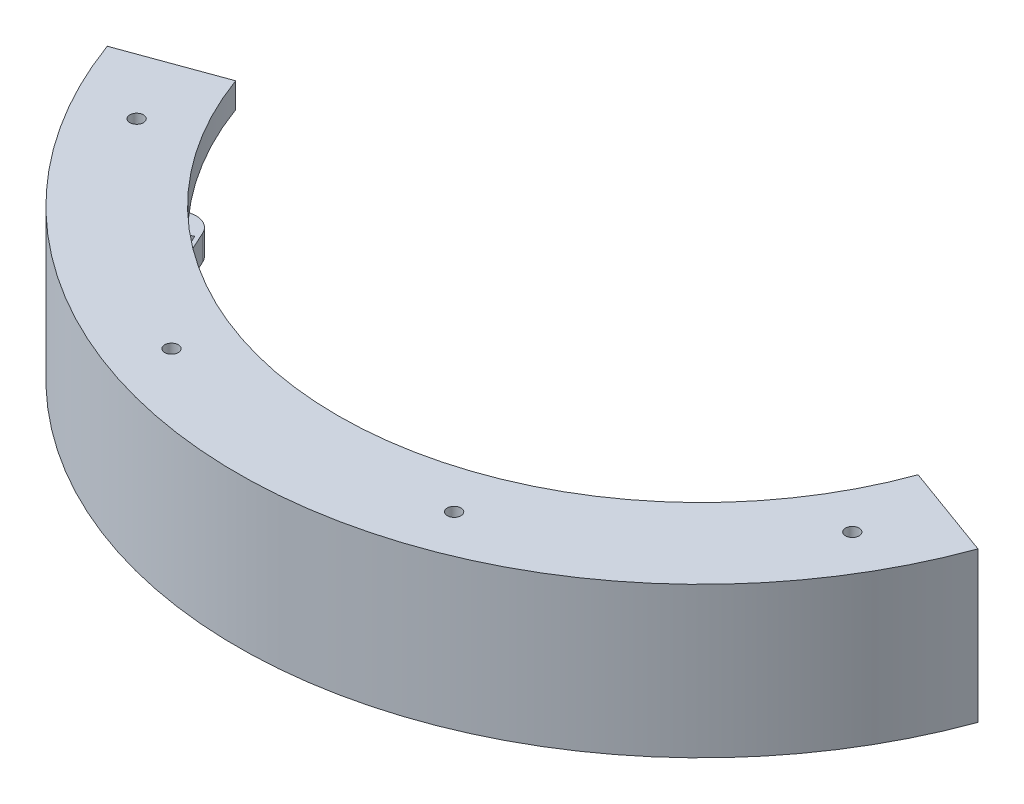
SolidWorks part; units mm, degrees
ref_plane "Front" through (0, 0, 0) normal (0, 0, 1) x (1, 0, 0)
ref_plane "Top" through (0, 0, 0) normal (0, 1, 0) x (1, 0, 0)
ref_plane "Right" through (0, 0, 0) normal (1, 0, 0) x (0, 0, -1)
sketch "Sketch1" plane through (0, 0, 0) normal (0, 1, 0) x (1, 0, 0)
  line L0 (-110.3904, -40.1788) -> (-86.5222, -31.4915)
  line L1 (86.5222, -31.4915) -> (110.3904, -40.1788)
  line L2 (-86.5222, -31.4915) -> (0, 0) construction
  line L3 (0, 0) -> (86.5222, -31.4915) construction
  line L4 (0, 0) -> (0, -117.475) construction
  line L5 (-86.5222, -31.4915) -> (0, -117.475) construction
  line L6 (0, -117.475) -> (86.5222, -31.4915) construction
  arc A0 (-110.3904, -40.1788) -> (110.3904, -40.1788) centre (0, 0) ccw
  arc A1 (-86.5222, -31.4915) -> (86.5222, -31.4915) centre (0, 0) ccw
  dimension "D1" = 25.4
  dimension "D2" = 117.475
  dimension "D3" = 140
extrude "Boss-Extrude1" add sketch "Sketch1" against normal blind 38.1
ref_plane "Plane1" through (86.5222, 0, 31.4915) normal (-0.342, 0, 0.9397) x (0.9397, 0, 0.342)
sketch "Sketch4" plane through (86.5222, 0, 31.4915) normal (-0.342, 0, 0.9397) x (0.9397, 0, 0.342)
  line L0 (0, -6.35) -> (19.05, -6.35)
  line L1 (0, -38.1) -> (0, 0) construction
  line L2 (19.05, -6.35) -> (19.05, -31.75)
  line L3 (19.05, -31.75) -> (0, -31.75)
  line L4 (0, -31.75) -> (0, -6.35)
  line L5 (25.4, -38.1) -> (25.4, 0) construction
  line L6 (25.4, -38.1) -> (0, -38.1) construction
  line L7 (25.4, 0) -> (0, 0) construction
  point P8 (12.7, -38.1)
  dimension "D1" = 6.35
  dimension "D2" = 6.35
  dimension "D3" = 6.35
ref_axis "Axis1" through (0, -38.1, 0) along (0, 1, 0)
revolve "Cut-Revolve1" cut sketch "Sketch4" about axis through (0, -38.1, 0) along (0, 1, 0)
sketch "Sketch5" plane through (0, -31.75, 0) normal (0, 1, 0) x (1, 0, 0)
  line L0 (98.3014, -45.3981) -> (88.6213, -40.6089)
  line L1 (98.3014, -45.3981) -> (95.7295, -50.5966)
  line L2 (95.7295, -50.5966) -> (86.0494, -45.8075)
  line L3 (86.0494, -45.8075) -> (88.6213, -40.6089)
  line L6 (0, 0) -> (105.2935, -52.0928) construction
  arc A0 (-110.3904, -40.1788) -> (110.3904, -40.1788) centre (0, 0) ccw construction
  arc A2 (-86.5222, -31.4915) -> (86.5222, -31.4915) centre (0, 0) ccw construction
  dimension "D1" = 5.8
  dimension "D2" = 10.8
  dimension "D3" = 2.9
  dimension "D4" = 97.4393
extrude "Cut-Extrude1" cut sketch "Sketch5" along normal up to surface (6.35 mm away)
pattern_circular "CirPattern1" count 13 every 11.667 about axis through (0, 0, 0) along (0, 1, 0) of "Cut-Extrude1"
sketch "Sketch10" plane through (0, 0, 0) normal (0, 1, 0) x (1, 0, 0)
  line L0 (0, 0) -> (101.7363, -58.7375) construction
  line L1 (39.1435, -14.2471) -> (133.9009, -48.7359) construction
  arc A0 (-110.3904, -40.1788) -> (110.3904, -40.1788) centre (0, 0) ccw construction
  circle A1 centre (0, 0) radius 104.775
  arc A2 (-86.5222, -31.4915) -> (86.5222, -31.4915) centre (0, 0) ccw construction
  dimension "D2" = 12.7
  dimension "D1" = 10
hole_wizard "#8-32 Tapped Hole1" positions "Sketch12" profile "Sketch11" tap size "#8-32" standard "ANSI Inch"
sketch "Sketch12" plane through (0, 0, 0) normal (0, 1, 0) x (1, 0, 0)
  line L0 (0, 0) -> (101.7363, -58.7375) construction
  circle A0 centre (0, 0) radius 104.775 construction
  point P0 (90.7378, -52.3875)
sketch "Sketch11" plane through (90.7378, 0, 52.3875) normal (1, 0, 0) x (0, 0, 1)
  line L0 (0, 0) -> (0, 11.7058)
  line L1 (0, 11.7058) -> (1.7272, 10.668)
  line L2 (1.7272, 10.668) -> (1.7272, 0)
  line L5 (1.7272, 0) -> (0, 0)
  line L10 (0, 11.7058) -> (-1.7272, 10.668) construction
  line L11 (0, -6.35) -> (0, 107.95) construction
  dimension "Tap Drill Dia." = 3.4544
  dimension "Tap Drill Depth" = 10.668
  dimension "Drill Angle" = 118
cosmetic thread "Hole Thread1" parameters "D1"=6.35, "D2"=4.1656
pattern_circular "CirPattern2" count 4 over 120 about axis through (0, 0, 0) along (0, 1, 0) of "#8-32 Tapped Hole1"
sketch "Sketch13" plane through (0, 0, 0) normal (0.342, 0, -0.9397) x (-0.9397, 0, -0.342)
  line L0 (-92.075, -31.75) -> (-92.075, -38.1)
  line L1 (-92.075, -38.1) -> (-96.527, -38.1)
  line L2 (-96.527, -38.1) -> (-96.527, -31.75)
  line L3 (85.1267, -31.75) -> (-111.125, -31.75) construction
  line L4 (-96.527, -31.75) -> (-92.075, -31.75)
revolve "Cut-Revolve2" cut sketch "Sketch13" angle 145 about axis through (0, -38.1, 0) along (0, 1, 0)
fillet "Fillet1" radius 5.08 2 edges at (90.7057, -34.925, 33.0142) (-90.7057, -34.925, 33.0142)
